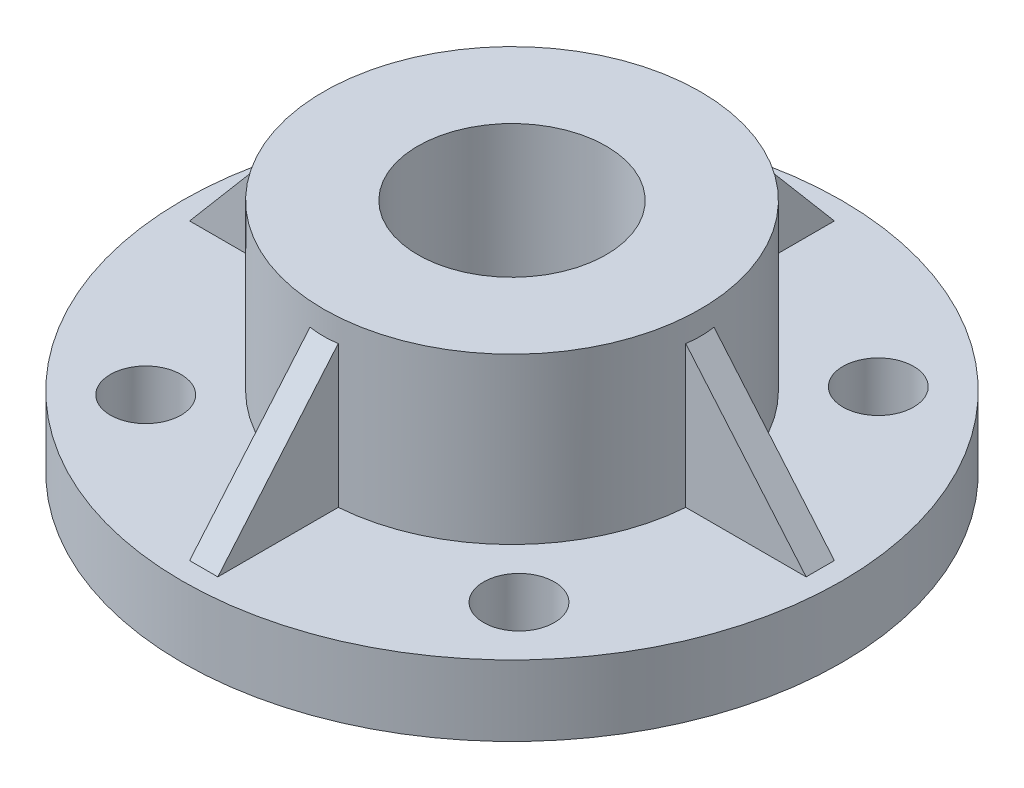
SolidWorks part; units mm, degrees
ref_plane "Front Plane" through (0, 0, 0) normal (0, 0, 1) x (1, 0, 0)
ref_plane "Top Plane" through (0, 0, 0) normal (0, 1, 0) x (1, 0, 0)
ref_plane "Right Plane" through (0, 0, 0) normal (1, 0, 0) x (0, 0, -1)
sketch "Sketch1" plane through (0, 0, 0) normal (0, 0, 1) x (1, 0, 0)
  line L0 (0, 0) -> (0, 199.1051) construction
  line L1 (20, 49.0898) -> (20, -0.9102)
  line L2 (20, -0.9102) -> (70, -0.9102)
  line L3 (20, 49.0898) -> (40, 49.0898)
  line L4 (40, 49.0898) -> (40, 14.0898)
  line L5 (40, 14.0898) -> (70, 14.0898)
  line L6 (70, 14.0898) -> (70, -0.9102)
  point P9 (0, 0)
  point P10 (0, 0)
  dimension "D1" = 50
  dimension "D2" = 15
  dimension "D3" = 20
  dimension "D4" = 50
  dimension "D5" = 20
revolve "Revolve1" add sketch "Sketch1" angle 360 about L0
sketch "Sketch2" plane through (0, 0, 0) normal (0, 0, 1) x (1, 0, 0)
  line L0 (-65, 14.6185) -> (-40, 44.0898)
  line L1 (-40, 49.0898) -> (-40, 14.0898) construction
  dimension "D1" = 5
  dimension "D2" = 5
rib "Rib1" sketch "Sketch2" sketch "Sketch2" thickness 6 extrusion direction parallel to sketch draft on no parameters "D1"=6
sketch "Sketch4" plane through (0, 0, 0) normal (0, 1, 0) x (1, 0, 0)
  line L0 (0, 71.6846) -> (0, -74.656) construction
  line L1 (-54.0565, 52.5708) -> (0, -1.4857) construction
  circle A0 centre (-39.6266, 38.1409) radius 7.5
  circle A1 centre (38.1409, 39.6266) radius 7.5
  circle A2 centre (39.6266, -38.1409) radius 7.5
  circle A3 centre (-38.1409, -39.6266) radius 7.5
  point P16 (0, 0)
  dimension "D2" = 15
  dimension "D4" = 4
  dimension "D1" = 45
  dimension "D3" = 55
extrude "Cut-Extrude2" cut sketch "Sketch4" along normal through all and the other way blind 10
pattern_circular "CirPattern6" count 4 over 360 about axis through (0, 0, 0) along (0, 1, 0) of "Rib1"
